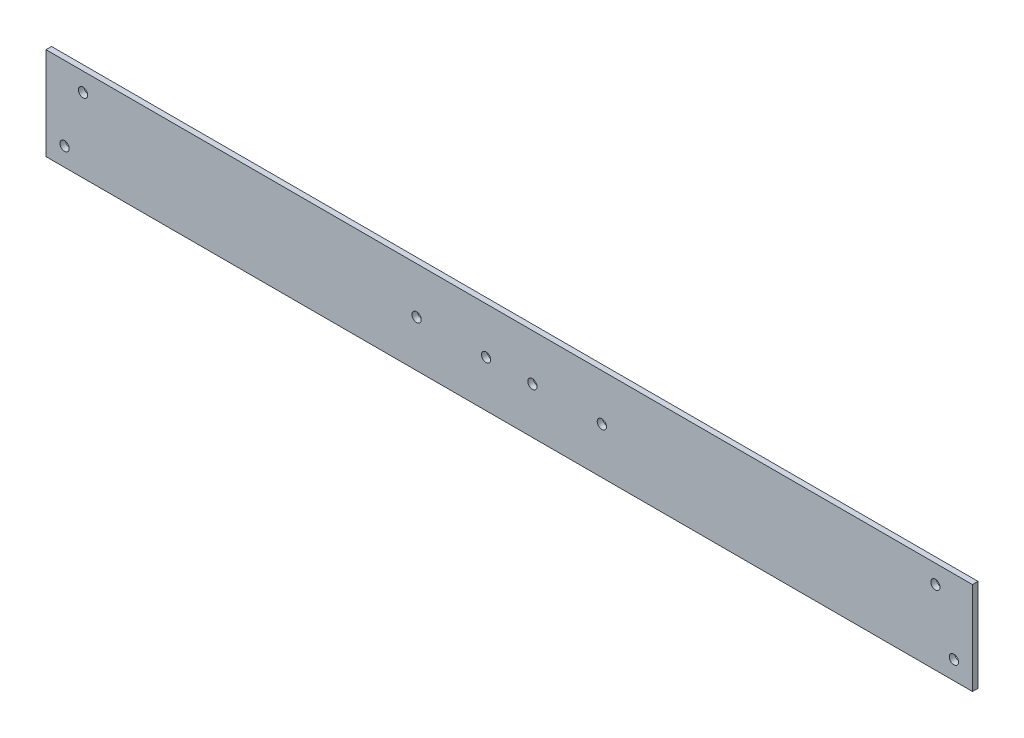
SolidWorks part; units mm, degrees
ref_plane "Front Plane" through (0, 0, 0) normal (0, 0, 1) x (1, 0, 0)
ref_plane "Top Plane" through (0, 0, 0) normal (0, 1, 0) x (1, 0, 0)
ref_plane "Right Plane" through (0, 0, 0) normal (1, 0, 0) x (0, 0, -1)
sketch "Sketch1" plane through (0, 0, 0) normal (0, 0, 1) x (1, 0, 0)
  line L0 (250, 50) -> (250, 0) construction
  line L1 (0, 0) -> (500, 0)
  line L2 (0, 0) -> (0, 50)
  line L3 (0, 50) -> (500, 50)
  line L4 (500, 0) -> (500, 50)
  circle A0 centre (20, 40) radius 2.5
  circle A2 centre (200, 25) radius 2.5
  circle A4 centre (237.5, 25) radius 2.5
  circle A8 centre (10, 10) radius 2.5
  circle A9 centre (262.5, 25) radius 2.5
  circle A10 centre (300, 25) radius 2.5
  circle A11 centre (480, 40) radius 2.5
  circle A12 centre (490, 10) radius 2.5
  point P11 (250, 50)
  dimension "D1" = 5
  dimension "D11" = 25
  dimension "D2" = 10
  dimension "D3" = 10
  dimension "D4" = 20
  dimension "D5" = 10
  dimension "D6" = 500
  dimension "D7" = 50
  dimension "D8" = 200
  dimension "D9" = 237.5
  dimension "D10" = 25
extrude "Boss-Extrude1" add sketch "Sketch1" along normal blind 3
